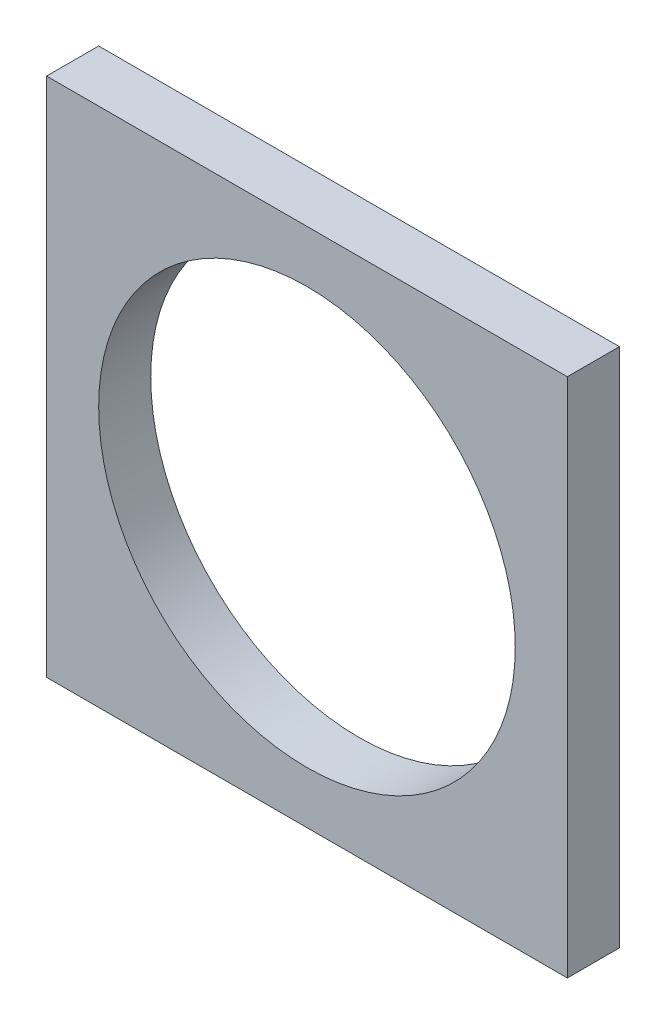
SolidWorks part; units mm, degrees
other "Static 1"
ref_plane "Спереди" through (0, 0, 0) normal (0, 0, 1) x (1, 0, 0)
ref_plane "Сверху" through (0, 0, 0) normal (0, 1, 0) x (1, 0, 0)
ref_plane "Справа" through (0, 0, 0) normal (1, 0, 0) x (0, 0, -1)
sketch "Sketch1" plane through (0, 0, 0) normal (0, 0, 1) x (1, 0, 0)
  line L1 (-50, 50) -> (-50, -50)
  line L2 (-50, -50) -> (50, -50)
  line L3 (50, -50) -> (50, 50)
  line L4 (50, 50) -> (-50, 50)
  circle A0 centre (0, 0) radius 50 construction
  circle A1 centre (0, 0) radius 40
  dimension "D2" = 80
  dimension "D1" = 100
extrude "Boss-Extrude1" add sketch "Sketch1" along normal blind 10
sketch3d "Трехмерный эскиз1"
  circle A0 centre (0, 0, 0) radius 40 construction
  point P0 (-35.7882, -17.8664, 0)
  point P3 (0, 0, 40)
